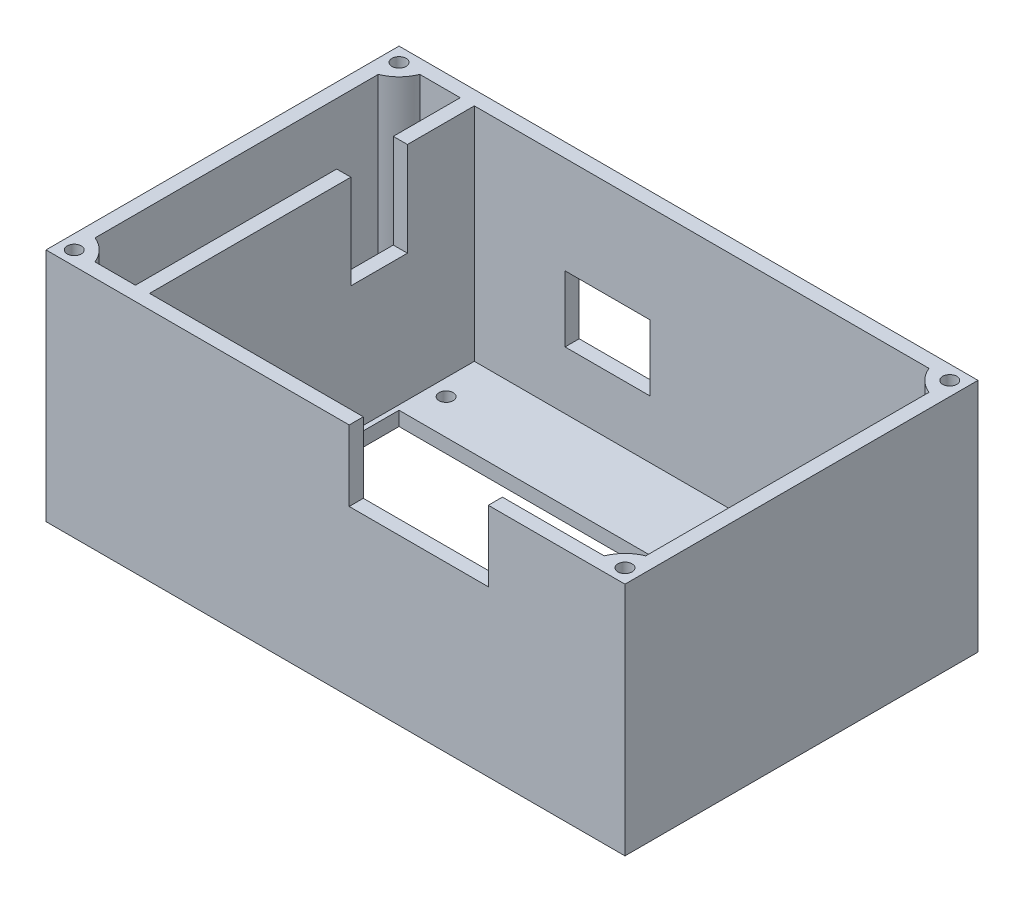
SolidWorks part; units mm, degrees
ref_plane "Спереди" through (0, 0, 0) normal (0, 0, 1) x (1, 0, 0)
ref_plane "Сверху" through (0, 0, 0) normal (0, 1, 0) x (1, 0, 0)
ref_plane "Справа" through (0, 0, 0) normal (1, 0, 0) x (0, 0, -1)
sketch "Эскиз1" plane through (0, 0, 0) normal (0, 1, 0) x (1, 0, 0)
  line L0 (-49, 20) -> (-49, -20)
  line L3 (49, -20) -> (49, 20)
  line L6 (0, 20) -> (-49, 20)
  line L7 (0, 20) -> (49, 20)
  line L8 (0, -20) -> (-49, -20)
  line L9 (0, -20) -> (49, -20)
  line L12 (54, -3.9493) -> (54, 40)
  line L13 (54, 40) -> (-69, 40)
  line L14 (-69, 40) -> (-69, -35)
  line L15 (-69, -35) -> (54, -35)
  line L16 (54, -35) -> (54, -3.9493)
  circle A0 centre (-46.5, 27.5) radius 1.5
  circle A1 centre (-46.5, -27.5) radius 1.5
  circle A2 centre (46.5, 27.5) radius 1.5
  circle A3 centre (46.5, -27.5) radius 1.5
extrude "Бобышка-Вытянуть1" add sketch "Эскиз1" along normal blind 3
sketch "Эскиз2" plane through (0, 3, 0) normal (0, 1, 0) x (1, 0, 0)
  line L0 (-50, -32) -> (51, -32)
  line L1 (-69, 40) -> (54, 40)
  line L2 (-69, 40) -> (-69, -35)
  line L3 (-69, -35) -> (54, -35)
  line L4 (54, 40) -> (54, -35)
  line L7 (-50, 0) -> (-50, 37)
  line L8 (-66, 37) -> (-53, 37)
  line L9 (-66, 37) -> (-66, -32)
  line L10 (-66, -32) -> (-53, -32)
  line L11 (51, 37) -> (51, -32)
  line L12 (-50, 0) -> (-50, -32)
  line L13 (-53, 0) -> (-53, 37)
  line L14 (-53, 0) -> (-53, -32)
  line L15 (-50, 37) -> (51, 37)
extrude "Бобышка-Вытянуть2" add sketch "Эскиз2" along normal blind 47
sketch "Эскиз3" plane through (0, 50, 0) normal (0, 1, 0) x (1, 0, 0)
  line L1 (-48.4919, 22.7829) -> (-55.1442, 22.7829)
  line L2 (-48.4919, 22.7829) -> (-48.4919, 10.7634)
  line L3 (-48.4919, 10.7634) -> (-55.1442, 10.7634)
  line L4 (-55.1442, 22.7829) -> (-55.1442, 10.7634)
extrude "Вырез-Вытянуть1" cut sketch "Эскиз3" against normal blind 20
sketch "Эскиз4" plane through (0, 50, 0) normal (0, 1, 0) x (1, 0, 0)
  line L0 (-69, 32) -> (-69, 40)
  line L1 (-69, 40) -> (-61, 40)
  line L2 (46, 40) -> (54, 40)
  line L3 (54, 40) -> (54, 32)
  line L4 (-69, -27) -> (-69, -35)
  line L5 (-69, -35) -> (-61, -35)
  line L6 (54, -27) -> (54, -35)
  line L7 (54, -35) -> (46, -35)
  arc A0 (-69, 32) -> (-61, 40) centre (-69, 40) ccw
  arc A1 (-61, -35) -> (-69, -27) centre (-69, -35) ccw
  arc A2 (46, 40) -> (54, 32) centre (54, 40) ccw
  arc A3 (54, -27) -> (46, -35) centre (54, -35) ccw
extrude "Бобышка-Вытянуть3" add sketch "Эскиз4" against normal up to surface (47 mm away) up to face at (0.5, 3, -2.5)
sketch "Эскиз5" plane through (0, 50, 0) normal (0, 1, 0) x (1, 0, 0)
  circle A2 centre (-66, 37) radius 1.5
  circle A3 centre (-66, -32) radius 1.5
  circle A4 centre (51, -32) radius 1.5
  circle A5 centre (51, 37) radius 1.5
extrude "Вырез-Вытянуть2" cut sketch "Эскиз5" against normal blind 10
sketch "Эскиз7" plane through (-69, 0, 0) normal (-1, 0, 0) x (0, 0, 1)
  line L0 (-16, 37) -> (-12, 37)
  line L2 (-16, 25) -> (2.0789, 25) construction
  line L3 (-16, 13) -> (-12, 13)
  line L6 (-16, 13) -> (-16, 37)
  line L8 (-12, 37) -> (-12, 13)
  point P2 (-12, 25)
extrude "Бобышка-Вытянуть4" add sketch "Эскиз7" along normal blind 8
sketch "Эскиз8" plane through (0, 0, -16) normal (0, 0, -1) x (-1, 0, 0)
  line L0 (77, 13) -> (69, 13) construction
  line L1 (77, 37) -> (73, 37)
  line L2 (77, 37) -> (77, 13)
  line L3 (77, 13) -> (73, 13)
  line L4 (73, 37) -> (73, 13)
extrude "Бобышка-Вытянуть5" add sketch "Эскиз8" along normal blind 10
sketch "Эскиз9" plane through (-69, 0, 0) normal (-1, 0, 0) x (0, 0, 1)
  line L0 (-26, 25) -> (4.2519, 25) construction
  line L1 (-26, 37) -> (-12, 37)
  line L2 (-26, 37) -> (-26, 41)
  line L3 (-26, 41) -> (-12, 41)
  line L4 (-12, 37) -> (-12, 41)
  line L5 (-26, 13) -> (-26, 37) construction
  line L6 (-12, 13) -> (-12, 9)
  line L7 (-26, 9) -> (-12, 9)
  line L8 (-26, 13) -> (-26, 9)
  line L9 (-26, 13) -> (-12, 13)
extrude "Бобышка-Вытянуть6" add sketch "Эскиз9" along normal blind 8
sketch "Эскиз10" plane through (0, 0, 35) normal (0, 0, 1) x (1, 0, 0)
  line L0 (-69, 50) -> (54, 50) construction
  line L1 (-4.5867, 50) -> (24.9644, 50)
  line L2 (-4.5867, 50) -> (-4.5867, 35)
  line L3 (-4.5867, 35) -> (24.9644, 35)
  line L4 (24.9644, 50) -> (24.9644, 35)
extrude "Вырез-Вытянуть3" cut sketch "Эскиз10" against normal blind 10
sketch "Эскиз11" plane through (0, 0, -40) normal (0, 0, -1) x (-1, 0, 0)
  line L1 (12.72, 29.2861) -> (30.72, 29.2861)
  line L2 (12.72, 29.2861) -> (12.72, 15.2861)
  line L3 (12.72, 15.2861) -> (30.72, 15.2861)
  line L4 (30.72, 29.2861) -> (30.72, 15.2861)
extrude "Вырез-Вытянуть4" cut sketch "Эскиз11" against normal blind 10 contours L1 L4 L3 L2
